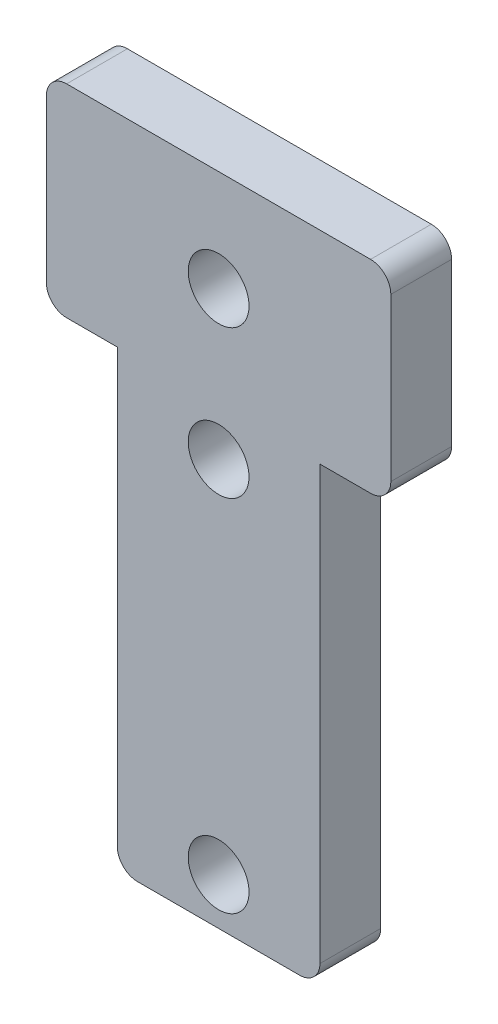
SolidWorks part; units mm, degrees
ref_plane "Front Plane" through (0, 0, 0) normal (0, 0, 1) x (1, 0, 0)
ref_plane "Top Plane" through (0, 0, 0) normal (0, 1, 0) x (1, 0, 0)
ref_plane "Right Plane" through (0, 0, 0) normal (1, 0, 0) x (0, 0, -1)
sketch "Sketch2" plane through (0, 0, 0) normal (0, 0, 1) x (1, 0, 0)
  line L1 (8.5, 5) -> (-8.5, 5)
  line L2 (8.5, 5) -> (8.5, -5)
  line L3 (8.5, -5) -> (-8.5, -5)
  line L4 (-8.5, 5) -> (-8.5, -5)
  line L5 (8.5, 5) -> (-8.5, -5) construction
  line L6 (8.5, -5) -> (-8.5, 5) construction
  line L8 (-5, -27.35) -> (5, -27.35)
  line L9 (-5, -27.35) -> (-5, -5)
  line L10 (-5, -5) -> (5, -5)
  line L11 (5, -27.35) -> (5, -5)
  line L12 (-5, -27.35) -> (5, -5) construction
  line L13 (-5, -5) -> (5, -27.35) construction
  circle A6 centre (0, 0) radius 1.5
  circle A9 centre (0, -7.3) radius 1.5
  circle A10 centre (0, -25.05) radius 1.5
  point P0 (0, 0)
  point P8 (0, -16.175)
  dimension "D2" = 5
  dimension "D3" = 7.3
  dimension "D4" = 3
  dimension "D5" = 25.05
  dimension "D10" = 3
  dimension "D11" = 3
  dimension "D12" = 17.75
  dimension "D6" = 22.35
  dimension "D7" = 10
  dimension "D8" = 10
  dimension "D9" = 17
  dimension "D13" = 12.3
extrude "Boss-Extrude1" add sketch "Sketch2" along normal blind 3
sketch3d "3DSketch1" plane through (0, 0, 0) normal (0, 0, 1) x (1, 0, 0)
fillet "Fillet5" radius 1 1 edges at (8.5, -5, 1.5)
fillet "Fillet6" radius 1 3 edges at (-8.5, -5, 1.5) (-5, -27.35, 1.5) (5, -27.35, 1.5)
fillet "Fillet7" radius 1 2 edges at (-8.5, 5, 1.5) (8.5, 5, 1.5)
